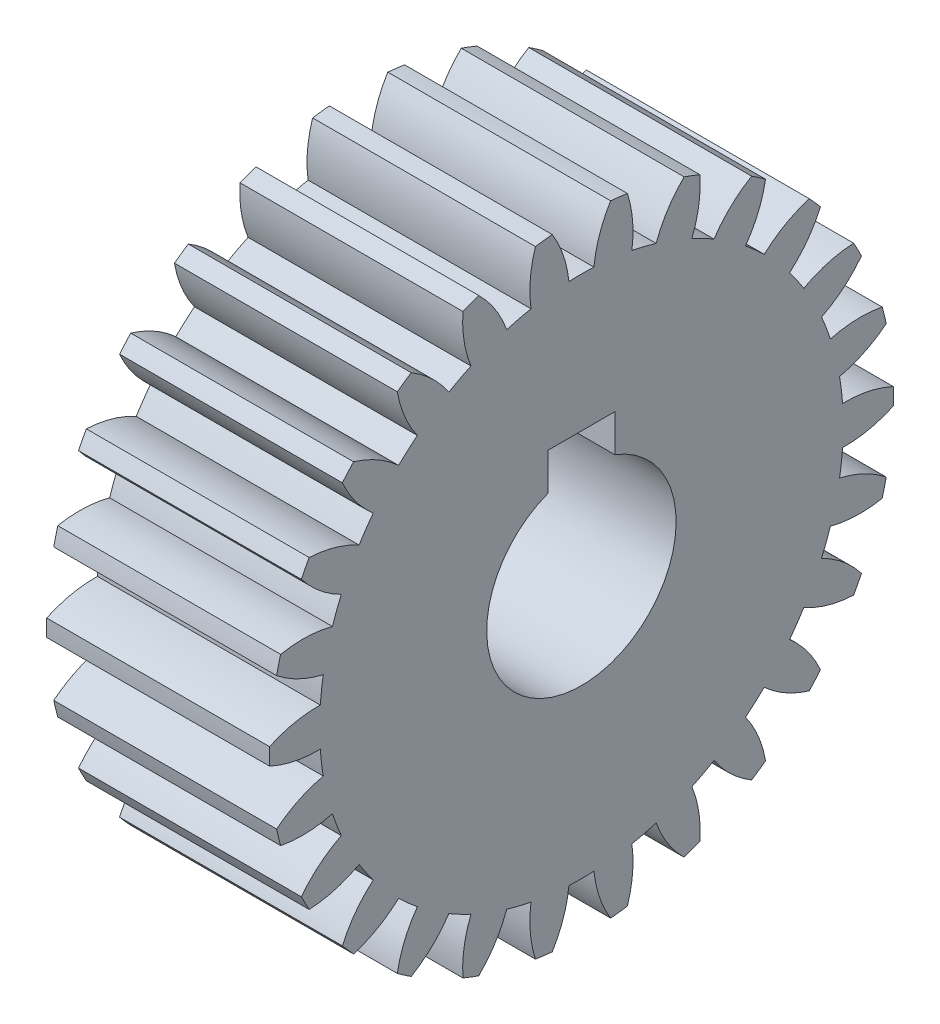
SolidWorks part; units mm, degrees
ref_plane "Plane1" through (0, 0, 0) normal (0, 0, 1) x (1, 0, 0)
ref_plane "Plane2" through (0, 0, 0) normal (0, 1, 0) x (1, 0, 0)
ref_plane "Plane3" through (0, 0, 0) normal (1, 0, 0) x (0, 0, -1)
sketch "HoldingSke" plane through (0, 0, 0) normal (0, 1, 0) x (1, 0, 0)
  line L0 (0, 0) -> (0.4494, -0.2192)
  line L1 (-15, 0) -> (100, 0) construction
  line L2 (0, 0) -> (-2.1039, 2.3779)
  line L3 (0, 0) -> (-11.863, 4.5341)
  line L4 (0, 0) -> (7.762, 3.7858)
  line L5 (0, 0) -> (-46.8476, -17.4728)
  line L6 (0, 0) -> (-16.5793, -11.1861)
  line L7 (-2.1039, 2.3779) -> (8.6586, 51.2059)
  line L8 (-76.2, 54.61) -> (-73.4, 54.61)
  line L9 (-67.7845, 28.3722) -> (-49.3413, 33.142)
  line L10 (-76.2, 71.12) -> (104.1128, 71.12)
  line L11 (0, 0) -> (-20, 0)
  line L12 (-76.2, 101.6) -> (-76.133, 101.6)
  line L13 (24.9733, 27.94) -> (52.9518, 28.4284)
  line L14 (24.9733, 27.94) -> (24.9743, 27.94)
  line L15 (24.9733, 27.94) -> (100.4006, 29.5858)
  line L16 (-63.627, -2) -> (-12.827, -2)
  circle A0 centre (0, 0) radius 8.5
  circle A1 centre (0, 0) radius 23.499
  circle A2 centre (0, 0) radius 37.5
  circle A3 centre (0, 0) radius 8.5
  dimension "MHD" = 46.998
  dimension "Hub_dia" = 75
  dimension "Bore" = 17
  dimension "MBD" = 17
  dimension "Num_teeth" = 26
  dimension "Pitch" = 0.5
  dimension "Overall_len" = 50
  dimension "Show_teeth" = 26
  dimension "Thickness" = 20
  dimension "OAL" = 50.0001
  dimension "T_dim" = 2.8
  dimension "Ap" = 14.5
  dimension "H" = 19.05
  dimension "Pitch_radius" = 180.3128
  dimension "Width" = 20
  dimension "Backlash" = 0.067
  dimension "Addendum_fac" = 1
  dimension "Dedendum_fac" = 1.25
  dimension "Clearance_fac" = 0.25
  dimension "Dedendum_add" = 0.001
  dimension "Module" = 2
sketch "BasProSke" plane through (0, 0, 0) normal (0, 1, 0) x (1, 0, 0)
  line L0 (-10, 0) -> (60, 0) construction
  line L1 (0, 0) -> (0, 28)
  line L2 (0, 0) -> (20, 0)
  line L3 (20, 0) -> (20, 28)
  line L4 (20, 28) -> (0, 28)
  dimension "Thickness" = 20
  dimension "Diameter" = 56
revolve "Base-Revolve" add sketch "BasProSke" angle 360 about L0
sketch "TooCutSke" plane through (0, 0, 0) normal (1, 0, 0) x (0, 0, -1)
  line L1 (0, 0) -> (0, 107) construction
  line L2 (0, 0) -> (-1.6871, 25.9452) construction
  line L3 (0, 0) -> (-6.2581, 51.5402) construction
  line L4 (-1.6871, 25.9452) -> (-3.1291, 25.7701) construction
  arc A0 (1.1217, 23.4722) -> (-1.1217, 23.4722) centre (0, 0) ccw
  arc A1 (2.6361, 27.9012) -> (-2.6361, 27.9012) centre (0, 0) ccw
  circle A2 centre (0, 0) radius 26 construction
  circle A3 centre (0, 0) radius 25.1718 construction
  arc A4 (-1.1217, 23.4722) -> (-2.6361, 27.9012) centre (-11.4671, 22.4082) ccw
  arc A5 (2.6361, 27.9012) -> (1.1217, 23.4722) centre (11.4671, 22.4082) ccw
  dimension "Root_dia" = 46.998
  dimension "Overcut_dia" = 56.0508
  dimension "Pitch_dia" = 52
  dimension "Base_dia" = 50.3437
  dimension "Flank_rad" = 10.4
  dimension "Half_ang" = 6.923
  dimension "Half_CT" = 1.4526
extrude "ToothCut" cut sketch "TooCutSke" along normal through all
fillet "Breaks" [suppressed] radius 0.04
fillet "RootFillets" [suppressed] radius 0.501
pattern_circular "TeethCuts" count 26 every 13.846 about axis through (-10, 0, 0) along (1, 0, 0) of "ToothCut", "RootFillets", "Breaks"
sketch "HubNeaOneSke" plane through (0, 0, 0) normal (-1, 0, 0) x (0, 0, 1)
  circle A0 centre (0, 0) radius 23.499
  dimension "Diameter" = 46.998
extrude "HubNearOne" [suppressed] add sketch "HubNeaOneSke" along normal blind 30.0001
sketch "HubNeaBotSke" plane through (0, 0, 0) normal (-1, 0, 0) x (0, 0, 1)
  circle A0 centre (0, 0) radius 23.499
  dimension "Diameter" = 46.998
extrude "HubNearBoth" [suppressed] add sketch "HubNeaBotSke" along normal blind 15
ref_plane "FarPln" through (20, 0, 0) normal (1, 0, 0) x (0, 0, -1)
sketch "HubFarSke" plane through (20, 0, 0) normal (1, 0, 0) x (0, 0, -1)
  circle A0 centre (0, 0) radius 23.499
  dimension "Diameter" = 46.998
extrude "HubFar" [suppressed] add sketch "HubFarSke" along normal blind 15
sketch "BorSke" plane through (0, 0, 0) normal (1, 0, 0) x (0, 0, -1)
  circle A0 centre (0, 0) radius 8.5
  dimension "Diameter" = 17
extrude "Bore" cut sketch "BorSke" along normal mid plane 100.0001
sketch "KeySke" plane through (0, 0, 0) normal (1, 0, 0) x (0, 0, -1)
  line L0 (-3, 0) -> (-3, 11.3)
  line L1 (-3, 11.3) -> (3, 11.3)
  line L2 (3, 11.3) -> (3, 0)
  line L3 (0, 0) -> (0, 34) construction
  line L4 (-3, 0) -> (3, 0)
  dimension "Offset" = 11.3
  dimension "Width" = 6
extrude "Keyway" cut sketch "KeySke" along normal mid plane 100.0001
pattern_circular "Keyway2" [suppressed] count 2 every 90 about axis through (-10, 0, 0) along (1, 0, 0)
equation "' \"Module@HoldingSke\" = 6.35"
equation "' \"Num_teeth@HoldingSke\" = 12"
equation "' \"Ap@HoldingSke\" =  20"
equation "' \"Ap@HoldingSke\" = 20"
equation "' \"Width@HoldingSke\" = 0.5 * 25.4"
equation "' \"Hub_dia@HoldingSke\"= 1 * 25.4"
equation "' \"Hub_dia@HoldingSke\" = 1 * 25.4"
equation "' \"Overall_len@HoldingSke\" = 1.0 * 25.4"
equation "' \"Bore@HoldingSke\" = 0.75 * 25.4"
equation "' \"T_dim@HoldingSke\" = 0.1 * 25.4"
equation "' \"Width@KeySke\" = 0.25 * 25.4"
equation "' \"Show_teeth@HoldingSke\" = 13"
equation "' \"Backlash@HoldingSke\" = 0.009 * 25.4"
equation "' \"Addendum_fac@HoldingSke\" = 1.0"
equation "' \"Dedendum_fac@HoldingSke\" = 1.25"
equation "' \"Dedendum_add@HoldingSke\" = 0.00005 * 25.4"
equation "' \"Clearance_fac@HoldingSke\" = 0.25"
equation "\"Pitch@HoldingSke\" = 1 / \"Module@HoldingSke\""
equation "\"Overcut_dia@TooCutSke\" = (\"Num_teeth@HoldingSke\" + 2 * \"Addendum_fac@HoldingSke\") / \"Pitch@HoldingSke\" + 0.002 * 25.4"
equation "\"Pitch_dia@TooCutSke\" = \"Num_teeth@HoldingSke\" / \"Pitch@HoldingSke\""
equation "\"Base_dia@TooCutSke\" = \"Num_teeth@HoldingSke\" / \"Pitch@HoldingSke\" * cos((\"Ap@HoldingSke\"  * 3.14159265 / 180))"
equation "\"Root_dia@TooCutSke\" = (\"Num_teeth@HoldingSke\" + 2) / \"Pitch@HoldingSke\" - 2 * (\"Addendum_fac@HoldingSke\" + \"Dedendum_fac@HoldingSke\") / \"Pitch@HoldingSke\" - \"Dedendum_add@HoldingSke\" * 2"
equation "\"Half_ang@TooCutSke\" = 180 / \"Num_teeth@HoldingSke\""
equation "\"Half_CT@TooCutSke\" = \"Num_teeth@HoldingSke\" / \"Pitch@HoldingSke\" * sin((3.14159265 / 2 / \"Num_teeth@HoldingSke\")) / 2 - 7 * \"Backlash@HoldingSke\" / 4"
equation "\"Flank_rad@TooCutSke\" = \"Num_teeth@HoldingSke\" / \"Pitch@HoldingSke\" / 5"
equation "\"Radius@RootFillets\" = \"Clearance_fac@HoldingSke\" / \"Pitch@HoldingSke\" + \"Dedendum_add@HoldingSke\""
equation "\"Break_rad@Breaks\" = 0.02 / \"Pitch@HoldingSke\""
equation "\"Thickness@HoldingSke\" = \"Width@HoldingSke\""
equation "\"OAL@HoldingSke\" = \"Thickness@HoldingSke\""
equation "\"MHD@HoldingSke\" = (\"Num_teeth@HoldingSke\" + 2) / \"Pitch@HoldingSke\" - 2 * (\"Addendum_fac@HoldingSke\" + \"Dedendum_fac@HoldingSke\")  / \"Pitch@HoldingSke\" - \"Dedendum_add@HoldingSke\" * 2"
equation "\"MBD@HoldingSke\" = (\"Num_teeth@HoldingSke\" + 2) / \"Pitch@HoldingSke\" - 2 * (\"Addendum_fac@HoldingSke\" + \"Dedendum_fac@HoldingSke\")  / \"Pitch@HoldingSke\" - \"Dedendum_add@HoldingSke\" * 2 - 0.002 * 25.4"
equation "\"MHD@HoldingSke\" = ((sgn( \"MHD@HoldingSke\" - \"Hub_dia@HoldingSke\" )-1)*( \"MHD@HoldingSke\" - \"Hub_dia@HoldingSke\" ))/-2+ \"Hub_dia@HoldingSke\""
equation "\"MBD@HoldingSke\" = ((sgn( \"MBD@HoldingSke\" - \"Bore@HoldingSke\" )-1)*( \"MBD@HoldingSke\" - \"Bore@HoldingSke\" ))/-2+ \"Bore@HoldingSke\""
equation "\"OAL@HoldingSke\" = ((sgn( \"OAL@HoldingSke\" - \"Overall_len@HoldingSke\" )+1)*( \"OAL@HoldingSke\" - \"Overall_len@HoldingSke\" ))/2 + \"Overall_len@HoldingSke\" + 0.000002 * 25.4"
equation "\"Num_teeth@TeethCuts\" = int( \"Show_teeth@HoldingSke\" ) + 1"
equation "\"Num_teeth@TeethCuts\" = ((sgn( \"Num_teeth@TeethCuts\" - \"Num_teeth@HoldingSke\" )-1)*( \"Num_teeth@TeethCuts\" - \"Num_teeth@HoldingSke\" ))/-2+ \"Num_teeth@HoldingSke\""
equation "\"Num_teeth@TeethCuts\" = ((sgn( \"Num_teeth@TeethCuts\" - 2.0)+1)*( \"Num_teeth@TeethCuts\" - 2.0))/2 +2.0"
equation "\"Angle@TeethCuts\" = 360.0 / \"Num_teeth@HoldingSke\""
equation "\"Diameter@BasProSke\" = (\"Num_teeth@HoldingSke\" + 2 * \"Addendum_fac@HoldingSke\") / \"Pitch@HoldingSke\""
equation "\"Thickness@BasProSke\"  = \"Thickness@HoldingSke\""
equation "' \"Fillet_rad@BasProSke\" =  \"Thickness@HoldingSke\" * 0.05"
equation "' \"Fillet_rad@BasProSke\" = \"Thickness@HoldingSke\" * 0.05"
equation "\"MHD@HoldingSke\" = ((sgn( \"MHD@HoldingSke\" - \"Root_dia@TooCutSke\" )-1)*( \"MHD@HoldingSke\" - \"Root_dia@TooCutSke\" ))/-2+ \"Root_dia@TooCutSke\""
equation "\"Diameter@HubNeaOneSke\" = \"MHD@HoldingSke\""
equation "\"Length@HubNearOne\" = \"OAL@HoldingSke\" - \"Thickness@BasProSke\""
equation "\"Diameter@HubNeaBotSke\" = \"MHD@HoldingSke\""
equation "\"Length@HubNearBoth\" = ( \"OAL@HoldingSke\" - \"Thickness@BasProSke\" ) / 2.0"
equation "\"Thickness@FarPln\" = \"Thickness@BasProSke\""
equation "\"Diameter@HubFarSke\" = \"MHD@HoldingSke\""
equation "\"Length@HubFar\" = ( \"OAL@HoldingSke\" - \"Thickness@BasProSke\" ) / 2.0"
equation "\"Diameter@BorSke\" = \"MBD@HoldingSke\""
equation "\"D1@Bore\" = \"OAL@HoldingSke\" * 2.0"
equation "\"D1@Keyway\" = \"OAL@HoldingSke\" * 2.0"
equation "\"Offset@KeySke\" = \"T_dim@HoldingSke\" + \"MBD@HoldingSke\" / 2.0"
